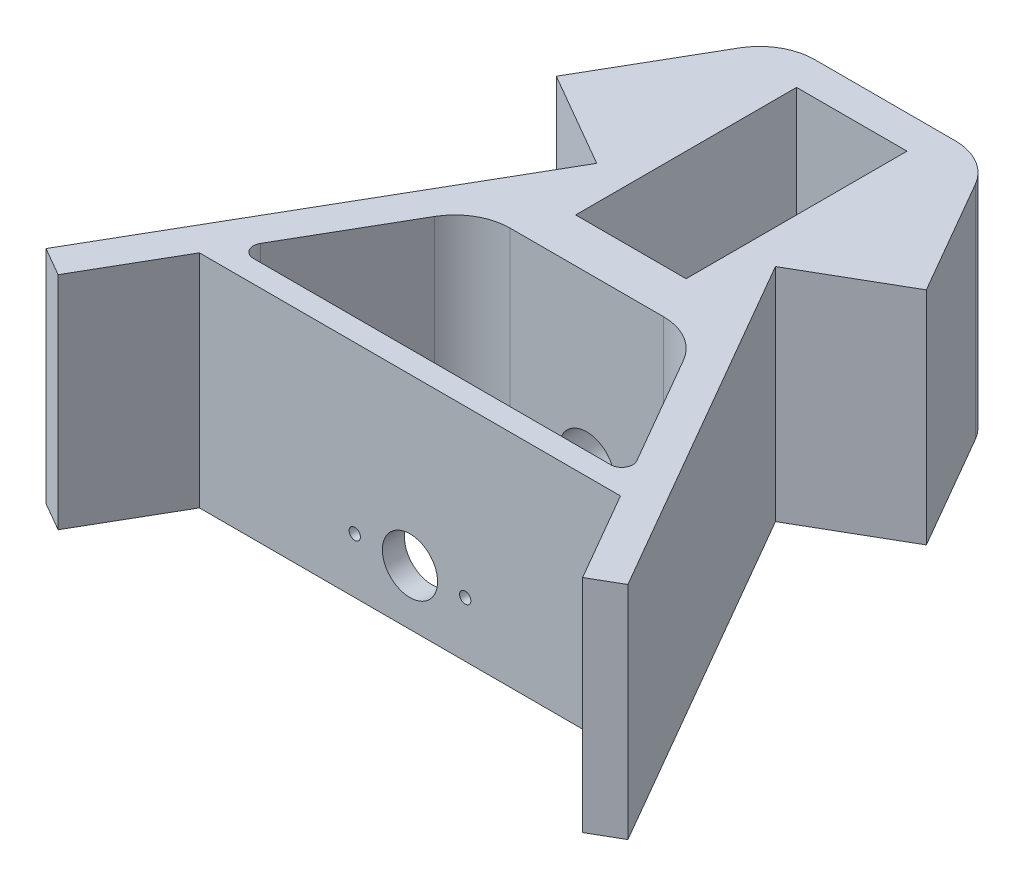
SolidWorks part; units mm, degrees
material "3.1355 (EN-AW 2024)"
ref_plane "Спереди" through (0, 0, 0) normal (0, 0, 1) x (1, 0, 0)
ref_plane "Сверху" through (0, 0, 0) normal (0, 1, 0) x (1, 0, 0)
ref_plane "Справа" through (0, 0, 0) normal (1, 0, 0) x (0, 0, -1)
sketch "Эскиз1" plane through (0, 0, 0) normal (0, 1, 0) x (1, 0, 0)
  line L12 (-38.1188, -50) -> (38.1188, -50)
  line L13 (38.1188, -50) -> (47.4833, -66.2199)
  line L14 (47.4833, -66.2199) -> (52.6795, -63.2199)
  line L15 (52.6795, -63.2199) -> (16.1795, 0)
  line L16 (16.1795, 0) -> (33.5, 10)
  line L17 (33.5, 10) -> (18.4889, 36)
  line L18 (18.4889, 36) -> (-18.4889, 36)
  line L19 (-18.4889, 36) -> (-33.5, 10)
  line L20 (-33.5, 10) -> (-16.1795, 0)
  line L21 (-16.1795, 0) -> (-52.6795, -63.2199)
  line L22 (-52.6795, -63.2199) -> (-47.4833, -66.2199)
  line L23 (-47.4833, -66.2199) -> (-38.1188, -50)
  line L24 (-35.8094, -46) -> (-19.6436, -18)
  line L25 (10, -10) -> (-10, -10)
  line L26 (10, -10) -> (10, 30)
  line L27 (10, 30) -> (-10, 30)
  line L28 (-10, -10) -> (-10, 30)
  line L29 (10, -10) -> (-10, 30) construction
  line L30 (10, 30) -> (-10, -10) construction
  line L31 (-19.6436, -18) -> (19.6436, -18)
  line L32 (19.6436, -18) -> (35.8094, -46)
  line L33 (35.8094, -46) -> (-35.8094, -46)
  point P11 (0, 36)
  point P13 (0, -50)
  point P14 (0, 10)
  point P24 (0, -18)
  point P25 (0, -46)
  dimension "D1" = 6
  dimension "D2" = 67
  dimension "D3" = 20
  dimension "D4" = 73
  dimension "D5" = 60
  dimension "D6" = 10
  dimension "D7" = 20
  dimension "D8" = 40
  dimension "D9" = 6
  dimension "D10" = 28
  dimension "D11" = 8
  dimension "D12" = 4
extrude "База" add sketch "Эскиз1" along normal mid plane 40
fillet "Скругление1" radius 10 4 edges at (19.6436, 0, 18) (-19.6436, 0, 18) (-18.4889, 0, -36) (18.4889, 0, -36)
fillet "Скругление2" radius 2 2 edges at (35.8094, 0, 46) (-35.8094, 0, 46)
sketch "Эскиз2" plane through (0, 0, 50) normal (0, 0, 1) x (1, 0, 0)
  circle A6 centre (0, -10) radius 5
  dimension "D1" = 10
  dimension "D2" = 10
extrude "Подшипник" cut sketch "Эскиз2" against normal up to surface (40 mm away) up to face at (0, 0, 10)
hole_wizard "Заглушка подшипника M2.5" positions "Эскиз3" profile "Эскиз4" tap size "M2.5" standard "ISO"
sketch "Эскиз3" plane through (0, 0, 50) normal (0, 0, 1) x (1, 0, 0)
  line L0 (-10, -10) -> (0, -10) construction
  line L1 (0, -10) -> (10, -10) construction
  point P0 (-10, -10)
  point P2 (10, -10)
  dimension "D1" = 20
  dimension "D2" = 10
sketch "Эскиз4" plane through (-10, -10, 50) normal (1, 0, 0) x (0, -1, 0)
  line L0 (0, 0) -> (0, 4.6149)
  line L1 (0, 4.6149) -> (1.025, 3.999)
  line L2 (1.025, 3.999) -> (1.025, 0)
  line L5 (1.025, 0) -> (0, 0)
  line L10 (0, 4.6149) -> (-1.025, 3.999) construction
  line L11 (0, -6.35) -> (0, 107.95) construction
  dimension "Диаметр сверла" = 2.05
  dimension "Глубина сверла" = 3.999
  dimension "Угол заточки сверла" = 118
cosmetic thread "Отверстие резьбы3" parameters "D1"=4, "D2"=2.5
cosmetic thread "Отверстие резьбы4" parameters "D1"=4, "D2"=2.5
